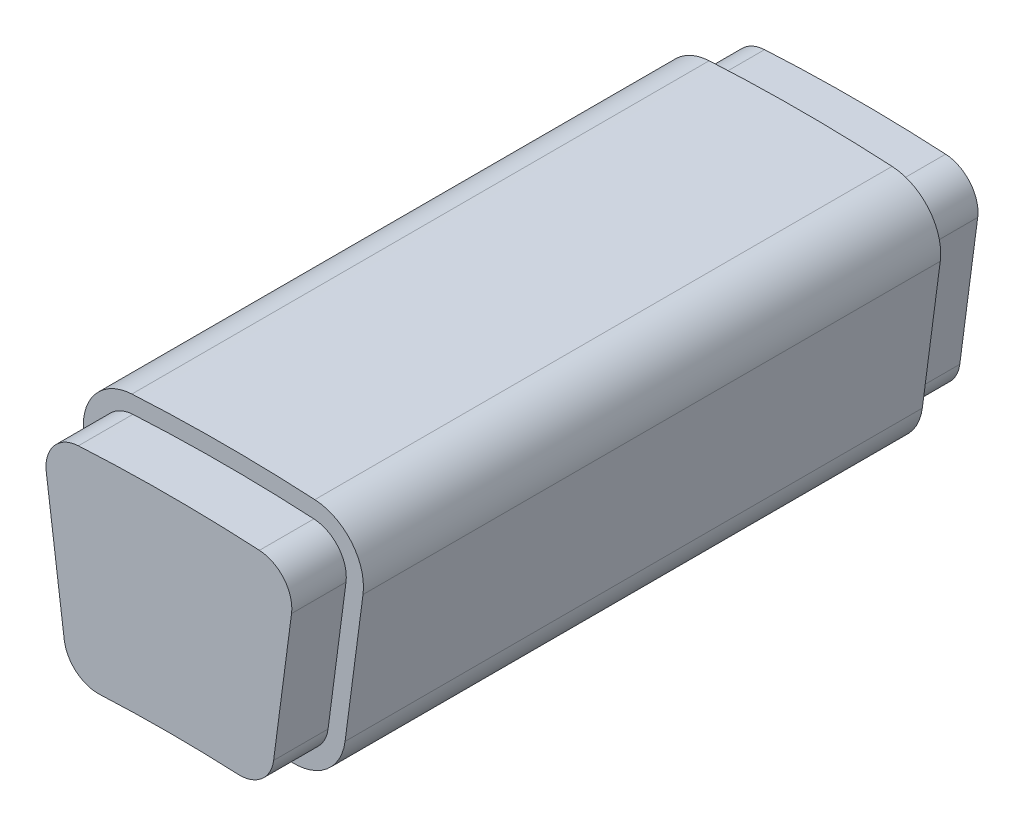
SolidWorks part; units mm, degrees
material "Plain Carbon Steel"
ref_plane "Front Plane" through (0, 0, 0) normal (0, 0, 1) x (1, 0, 0)
ref_plane "Top Plane" through (0, 0, 0) normal (0, 1, 0) x (1, 0, 0)
ref_plane "Right Plane" through (0, 0, 0) normal (1, 0, 0) x (0, 0, -1)
sketch "Sketch1" plane through (0, 0, 0) normal (0, 0, 1) x (1, 0, 0)
  line L3 (6.1032, 84.6647) -> (7.1481, 92.602)
  line L4 (-7.1481, 92.602) -> (-6.1032, 84.6647)
  line L5 (6.1032, 84.6647) -> (7.1481, 92.602)
  line L6 (-7.1481, 92.602) -> (-6.1032, 84.6647)
  arc A6 (5.2763, 94.86) -> (-5.2763, 94.86) centre (0, 0) ccw
  arc A7 (7.1481, 92.602) -> (5.2763, 94.86) centre (5.1652, 92.863) ccw
  arc A8 (4.0234, 82.9281) -> (6.1032, 84.6647) centre (4.1203, 84.9257) ccw
  arc A9 (4.0234, 82.9281) -> (-4.0234, 82.9281) centre (0, 0) ccw
  arc A10 (-6.1032, 84.6647) -> (-4.0234, 82.9281) centre (-4.1203, 84.9257) ccw
  arc A11 (-5.2763, 94.86) -> (-7.1481, 92.602) centre (-5.1652, 92.863) ccw
  arc A12 (5.2763, 94.86) -> (-5.2763, 94.86) centre (0, 0) ccw
  arc A13 (7.1481, 92.602) -> (5.2763, 94.86) centre (5.1652, 92.863) ccw
  arc A14 (4.0234, 82.9281) -> (6.1032, 84.6647) centre (4.1203, 84.9257) ccw
  arc A15 (4.0234, 82.9281) -> (-4.0234, 82.9281) centre (0, 0) ccw
  arc A16 (-6.1032, 84.6647) -> (-4.0234, 82.9281) centre (-4.1203, 84.9257) ccw
  arc A17 (-5.2763, 94.86) -> (-7.1481, 92.602) centre (-5.1652, 92.863) ccw
  dimension "D1" = 0
extrude "Boss-Extrude1" add sketch "Sketch1" against normal up to vertex (3.175 mm away) and the other way up to vertex (36.825 mm away)
sketch "Sketch2" plane through (0, 0, 0) normal (0, 0, 1) x (1, 0, 0)
  line L4 (7.0946, 84.5341) -> (8.1396, 92.4715)
  line L5 (-8.1396, 92.4715) -> (-7.0946, 84.5341)
  line L6 (7.0946, 84.5341) -> (8.1396, 92.4715)
  line L7 (-8.1396, 92.4715) -> (-7.0946, 84.5341)
  arc A12 (8.1396, 92.4715) -> (5.3319, 95.8584) centre (5.1652, 92.863) ccw
  arc A13 (3.9749, 81.9292) -> (7.0946, 84.5341) centre (4.1203, 84.9257) ccw
  arc A14 (3.9749, 81.9292) -> (-3.9749, 81.9292) centre (0, 0) ccw
  arc A15 (-7.0946, 84.5341) -> (-3.9749, 81.9292) centre (-4.1203, 84.9257) ccw
  arc A16 (-5.3319, 95.8584) -> (-8.1396, 92.4715) centre (-5.1652, 92.863) ccw
  arc A17 (5.3319, 95.8584) -> (-5.3319, 95.8584) centre (0, 0) ccw
  arc A18 (8.1396, 92.4715) -> (5.3319, 95.8584) centre (5.1652, 92.863) ccw
  arc A19 (3.9749, 81.9292) -> (7.0946, 84.5341) centre (4.1203, 84.9257) ccw
  arc A20 (3.9749, 81.9292) -> (-3.9749, 81.9292) centre (0, 0) ccw
  arc A21 (-7.0946, 84.5341) -> (-3.9749, 81.9292) centre (-4.1203, 84.9257) ccw
  arc A22 (-5.3319, 95.8584) -> (-8.1396, 92.4715) centre (-5.1652, 92.863) ccw
  arc A23 (5.3319, 95.8584) -> (-5.3319, 95.8584) centre (0, 0) ccw
  dimension "D1" = 1
extrude "Boss-Extrude2" add sketch "Sketch2" along normal up to vertex (33.65 mm away)
